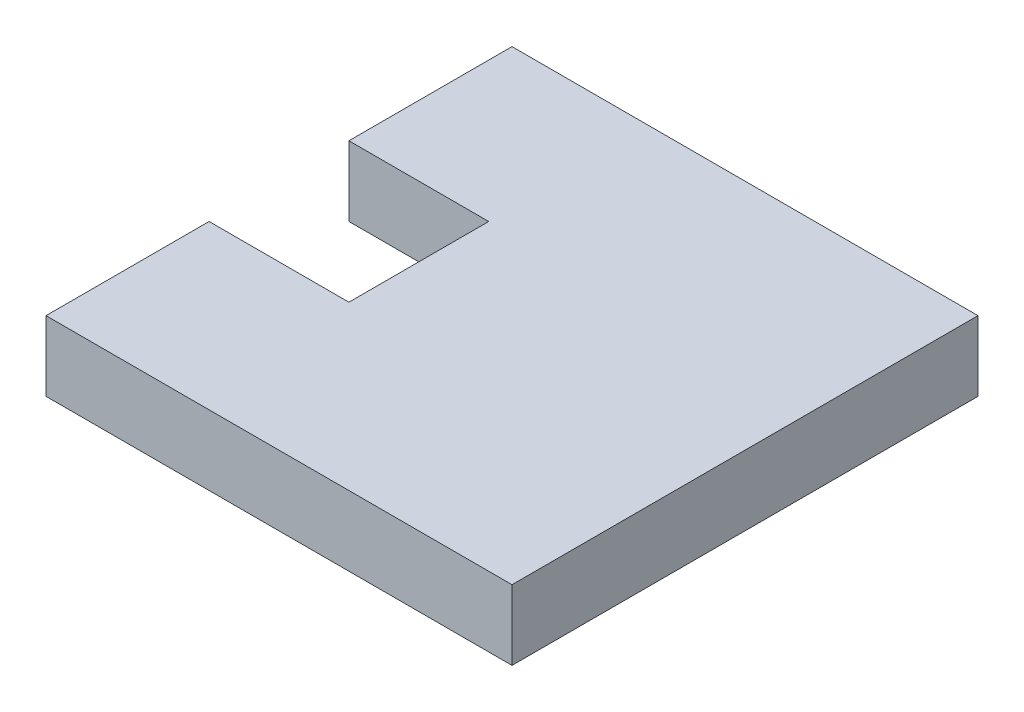
SolidWorks part; units mm, degrees
material "Alu Künz"
ref_plane "Ebene vorne" through (0, 0, 0) normal (0, 0, 1) x (1, 0, 0)
ref_plane "Ebene oben" through (0, 0, 0) normal (0, 1, 0) x (1, 0, 0)
ref_plane "Ebene rechts" through (0, 0, 0) normal (1, 0, 0) x (0, 0, -1)
sketch "Skizze1" plane through (0, 0, 0) normal (0, 0, 1) x (1, 0, 0)
  line L7 (-50, -7.5) -> (50, 7.5) construction
  line L8 (-50, 7.5) -> (50, 7.5)
  line L9 (-50, 7.5) -> (-50, -7.5)
  line L10 (-50, -7.5) -> (50, -7.5)
  line L11 (50, 7.5) -> (50, -7.5)
  dimension "D1" = 15
  dimension "D2" = 100
extrude "Aufsatz-Linear austragen1" add sketch "Skizze1" along normal mid plane 100
sketch "Skizze2" plane through (0, 0, 0) normal (0, 1, 0) x (1, 0, 0)
  line L0 (-50, -50) -> (-50, 50) construction
  line L1 (-50, 15) -> (-20, 15)
  line L2 (-50, 15) -> (-50, -15)
  line L3 (-50, -15) -> (-20, -15)
  line L4 (-20, 15) -> (-20, -15)
  line L5 (-50, 0) -> (0, 0) construction
  dimension "D1" = 30
  dimension "D2" = 30
extrude "Schnitt-Linear austragen1" cut sketch "Skizze2" against normal through all both and the other way through all
